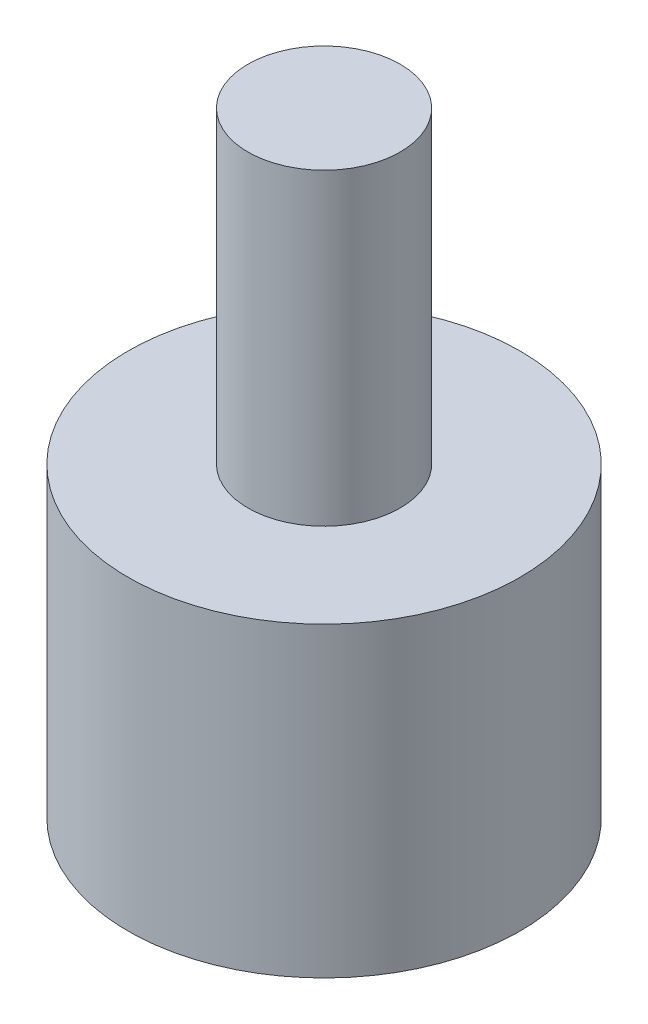
SolidWorks part; units mm, degrees
material "1023 Tôle d'acier au carbone (SS)"
ref_plane "Plan de face" through (0, 0, 0) normal (0, 0, 1) x (1, 0, 0)
ref_plane "Plan de dessus" through (0, 0, 0) normal (0, 1, 0) x (1, 0, 0)
ref_plane "Plan de droite" through (0, 0, 0) normal (1, 0, 0) x (0, 0, -1)
sketch "Esquisse1" plane through (0, 0, 0) normal (0, 0, 1) x (1, 0, 0)
  line L0 (0, -22.9394) -> (0, 59.2358) construction
  line L1 (5.6745, 3.5) -> (10.3, 3.5)
  line L2 (10.3, 3.5) -> (10.3, 19.6)
  line L3 (10.3, 19.6) -> (4, 19.6)
  line L4 (4, 19.6) -> (4, 35.8)
  line L5 (4, 35.8) -> (0, 35.8)
  line L6 (0, 35.8) -> (0, 0)
  arc A0 (0, 0) -> (5.6745, 3.5) centre (0, 6.35) ccw
  dimension "D1" = 6.35
  dimension "D2" = 16.1
  dimension "D3" = 20.6
  dimension "D4" = 16.2
  dimension "D5" = 35.8
  dimension "D6" = 8
revolve "Révolution1" add sketch "Esquisse1" angle 360 about L0
